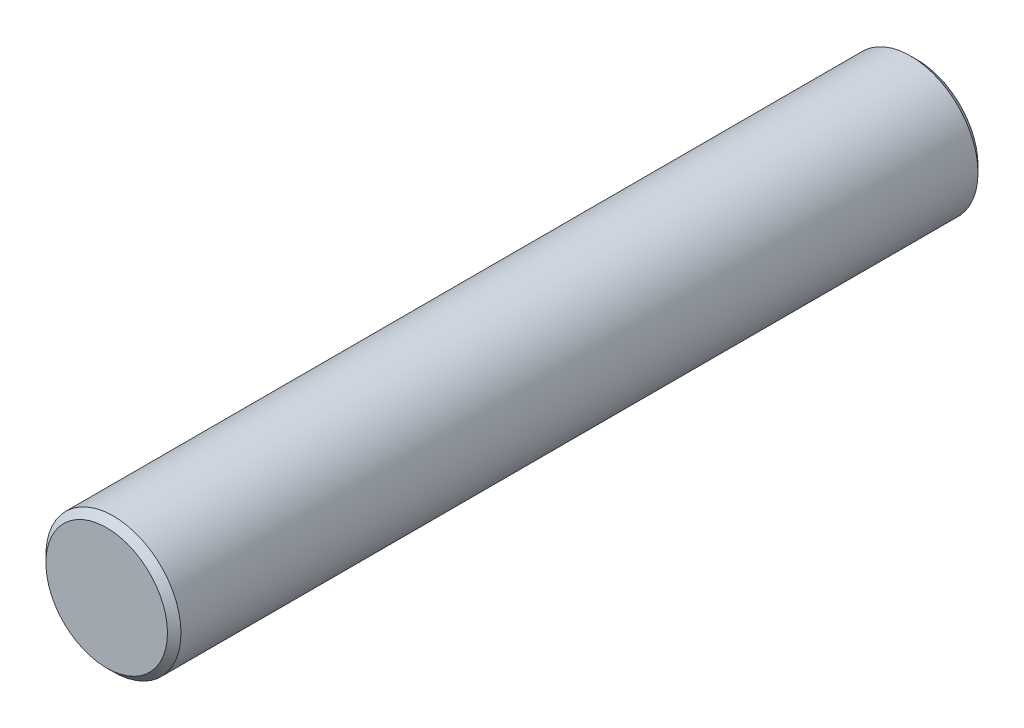
SolidWorks part; units mm, degrees
ref_plane "Front Plane" through (0, 0, 0) normal (0, 0, 1) x (1, 0, 0)
ref_plane "Top Plane" through (0, 0, 0) normal (0, 1, 0) x (1, 0, 0)
ref_plane "Right Plane" through (0, 0, 0) normal (1, 0, 0) x (0, 0, -1)
sketch "Sketch2" plane through (0, 0, 0) normal (0, 0, 1) x (1, 0, 0)
  circle A0 centre (0, 0) radius 2.5
  dimension "D1" = 5
extrude "Boss-Extrude1" add sketch "Sketch2" along normal mid plane 30
chamfer "Chamfer1" distance 0.25 angle 45 2 edges at (2.5, 0, -15) (2.5, 0, 15)
